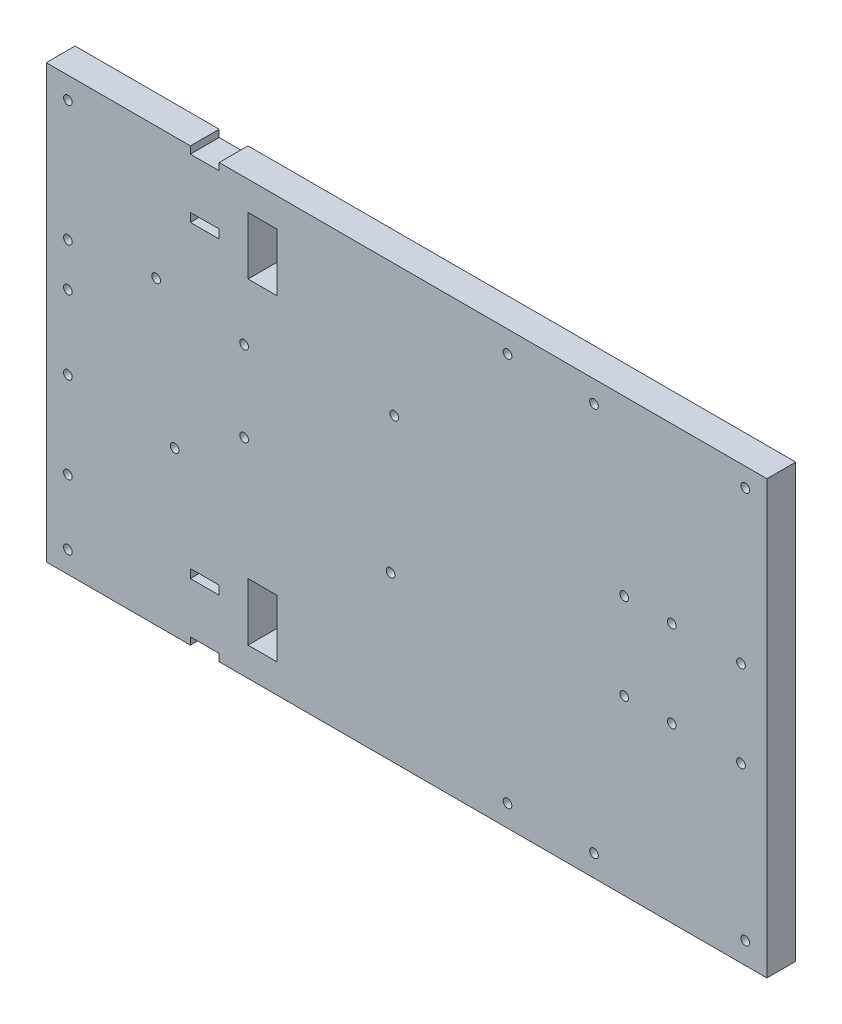
SolidWorks part; units mm, degrees
ref_plane "Front" through (0, 0, 0) normal (0, 0, 1) x (1, 0, 0)
ref_plane "Top" through (0, 0, 0) normal (0, 1, 0) x (1, 0, 0)
ref_plane "Right" through (0, 0, 0) normal (1, 0, 0) x (0, 0, -1)
sketch "Sketch1" plane through (0, 0, 0) normal (0, 0, 1) x (1, 0, 0)
  line L0 (-75, -55) -> (-65, -55)
  line L1 (-125, -75) -> (-75, -75)
  line L2 (-125, -75) -> (-125, 75)
  line L3 (-125, 75) -> (-75, 75)
  line L4 (125, -75) -> (125, 75)
  line L5 (-75, 55) -> (-65, 55)
  line L6 (-75, 55) -> (-75, 52)
  line L7 (-75, 52) -> (-65, 52)
  line L8 (-65, 55) -> (-65, 52)
  line L9 (-75, -55) -> (-75, -52)
  line L10 (-75, -52) -> (-65, -52)
  line L11 (-65, -55) -> (-65, -52)
  line L12 (-55, -45) -> (-45, -45)
  line L13 (-55, -45) -> (-55, -65)
  line L14 (-55, 65) -> (-45, 65)
  line L15 (-55, 65) -> (-55, 45)
  line L16 (-55, 45) -> (-45, 45)
  line L17 (-45, 65) -> (-45, 45)
  line L18 (-55, -65) -> (-45, -65)
  line L19 (-45, -45) -> (-45, -65)
  line L20 (-25, -75) -> (-15, -75)
  line L21 (-25, 75) -> (-15, 75)
  line L22 (-75, -75) -> (-75, -72.5)
  line L23 (-75, -72.5) -> (-65, -72.5)
  line L24 (-65, -72.5) -> (-65, -75)
  line L25 (-65, -75) -> (-25, -75)
  line L26 (-75, 75) -> (-75, 72.5)
  line L27 (-75, 72.5) -> (-65, 72.5)
  line L28 (-65, 72.5) -> (-65, 75)
  line L29 (-65, 75) -> (-25, 75)
  line L45 (-15, 75) -> (125, 75)
  line L46 (-15, -75) -> (125, -75)
  circle A0 centre (75.5, 15) radius 1.5
  circle A1 centre (75.5, -15) radius 1.5
  circle A2 centre (-117.5, -15) radius 1.5
  circle A3 centre (-117.5, -45) radius 1.5
  circle A4 centre (35.0103, -67.5) radius 1.5
  circle A5 centre (65.0103, -67.5) radius 1.5
  circle A6 centre (35.0103, 67.5) radius 1.5
  circle A7 centre (65.0103, 67.5) radius 1.5
  circle A8 centre (-117.5, 25.5735) radius 1.5
  circle A9 centre (-117.5, 10.5735) radius 1.5
  circle A10 centre (-5.5594, -18.4953) radius 1.5
  circle A11 centre (-80.4594, -18.4953) radius 1.5
  circle A12 centre (-86.8594, 29.3047) radius 1.5
  circle A13 centre (-4.2594, 29.3047) radius 1.5
  circle A14 centre (-56.3594, 24.6047) radius 1.5
  circle A15 centre (-56.3594, -3.2953) radius 1.5
  circle A16 centre (92, 15) radius 1.5
  circle A17 centre (116, 15) radius 1.5
  circle A18 centre (116, -15) radius 1.5
  circle A19 centre (92, -15) radius 1.5
  circle A20 centre (-117.5, 67.5) radius 1.5
  circle A21 centre (117.5, 68.5) radius 1.5
  circle A22 centre (117.5, -67.5) radius 1.5
  circle A23 centre (-117.5, -67.5) radius 1.5
  point P63 (0, 0)
extrude "Boss-Extrude1" add sketch "Sketch1" along normal blind 10
